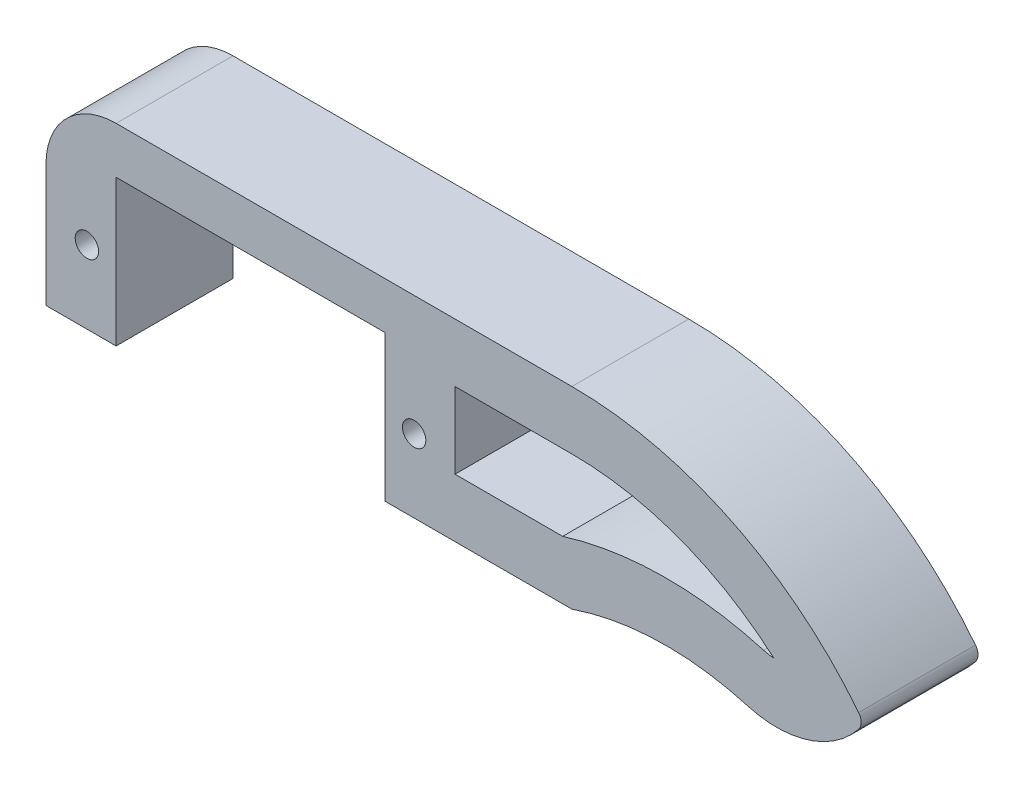
SolidWorks part; units mm, degrees
ref_plane "Alzado" through (0, 0, 0) normal (0, 0, 1) x (1, 0, 0)
ref_plane "Planta" through (0, 0, 0) normal (0, 1, 0) x (1, 0, 0)
ref_plane "Vista lateral" through (0, 0, 0) normal (1, 0, 0) x (0, 0, -1)
sketch "Croquis1" plane through (0, 0, 0) normal (0, 0, 1) x (1, 0, 0)
  line L1 (0, 0) -> (6, 0)
  line L2 (0, 0) -> (0, 16.5)
  line L3 (0, 16.5) -> (35, 16.5)
  line L4 (35, 0) -> (35, 16.5)
  line L5 (29, 12.5) -> (6, 12.5)
  line L6 (29, 12.5) -> (29, 0)
  line L7 (29, 0) -> (6, 0)
  line L8 (6, 12.5) -> (6, 0)
  line L10 (29, 0) -> (35, 0)
  circle A0 centre (3.5, 6.25) radius 1
  circle A1 centre (31.5, 6.25) radius 1
  point P10 (6, 6.25)
  point P11 (17.5, 16.5)
  point P12 (17.5, 12.5)
  dimension "D5" = 2
  dimension "D7" = 2.5
  dimension "D1" = 23
  dimension "D2" = 6
  dimension "D3" = 12.5
  dimension "D4" = 4
  dimension "D6" = 2.5
extrude "Saliente-Extruir1" add sketch "Croquis1" against normal blind 10
sketch "Croquis4" plane through (0, 0, 0) normal (0, 0, 1) x (1, 0, 0)
  line L1 (45, 11.5) -> (35, 11.5)
  line L5 (45, 0) -> (35, 0)
  line L8 (45, 16.5) -> (35, 16.5)
  line L9 (35, 0) -> (35, 16.5) construction
  line L10 (44.2095, 5) -> (35, 5)
  line L11 (35, 16.5) -> (35, 11.5)
  line L12 (35, 5) -> (35, 0)
  arc A0 (70, 4) -> (60.0163, 0.3543) centre (62.5167, 9) cw
  arc A1 (45, 16.5) -> (70, 4) centre (45, -14.75) cw
  arc A2 (60.0163, 0.3543) -> (45, 0) centre (53.0706, -23.6615) ccw
  arc A3 (45, 11.5) -> (62.2839, 5.0068) centre (45, -14.75) cw
  arc A4 (62.2839, 5.0068) -> (61.4054, 5.1575) centre (62.5167, 9) cw
  arc A5 (61.4054, 5.1575) -> (44.2095, 5) centre (53.0706, -23.6615) ccw
  dimension "D4" = 4
  dimension "D5" = 25
  dimension "D6" = 9
  dimension "D1" = 10
  dimension "D2" = 10
  dimension "D3" = 35
  dimension "D7" = 5
extrude "Saliente-Extruir2" add sketch "Croquis4" against normal through all
fillet "Redondeo1" radius 1 1 edges at (70, 4, -5)
fillet "Redondeo2" radius 6 1 edges at (0, 16.5, -5)
